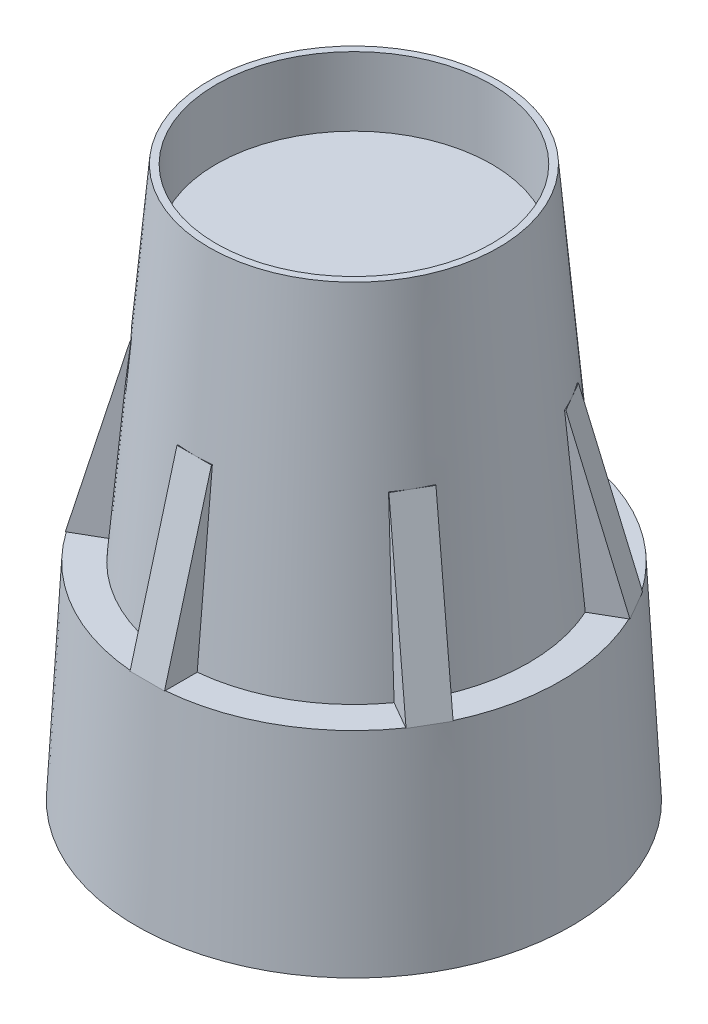
SolidWorks part; units mm, degrees
ref_plane "Front Plane" through (0, 0, 0) normal (0, 0, 1) x (1, 0, 0)
ref_plane "Top Plane" through (0, 0, 0) normal (0, 1, 0) x (1, 0, 0)
ref_plane "Right Plane" through (0, 0, 0) normal (1, 0, 0) x (0, 0, -1)
sketch "Sketch1" plane through (0, 0, 0) normal (0, 1, 0) x (1, 0, 0)
  circle A0 centre (0, 0) radius 21
  dimension "D1" = 42
extrude "Boss-Extrude1" add sketch "Sketch1" against normal blind 50 draft 5 draft outward yes
sketch "Sketch2" plane through (0, -50, 0) normal (0, -1, 0) x (1, 0, 0)
  circle A0 centre (0, 0) radius 30
  dimension "D1" = 60
extrude "Boss-Extrude2" add sketch "Sketch2" along normal blind 30 draft 3 draft outward yes
sketch "Sketch3" plane through (0, 0, 0) normal (1, 0, 0) x (0, 0, -1)
  line L1 (-21, 0) -> (-25.3744, -50) construction
  line L2 (-25.3744, -50) -> (-30, -50)
  line L3 (-30, -50) -> (-23.1872, -25)
  line L4 (-23.1872, -25) -> (-20.2805, -25)
  line L5 (-20.2805, -25) -> (-22.4677, -50)
  line L6 (30, -50) -> (-30, -50) construction
  line L7 (-22.4677, -50) -> (-25.3744, -50)
extrude "Boss-Extrude3" add sketch "Sketch3" along normal mid plane 5
pattern_circular "CirPattern1" count 6 every 60 about axis through (0, 0, 0) along (0, 1, 0) of "Boss-Extrude3"
sketch "Sketch4" plane through (0, -80, 0) normal (0, -1, 0) x (1, 0, 0)
  circle A0 centre (0, 0) radius 27.2913
  circle A1 centre (0, 0) radius 23.5946
extrude "Cut-Extrude1" cut sketch "Sketch4" against normal blind 3 draft 10 contours A0 A1
sketch "Sketch5" plane through (0, -80, 0) normal (0, -1, 0) x (1, 0, 0)
  circle A0 centre (0, 0) radius 19.3823
  circle A1 centre (0, 0) radius 16.1728
extrude "Cut-Extrude2" cut sketch "Sketch5" against normal blind 2.5 draft 10 contours A0 A1
sketch "Sketch6" plane through (0, -80, 0) normal (0, -1, 0) x (1, 0, 0)
  circle A0 centre (0, 0) radius 10.9258
extrude "Boss-Extrude4" add sketch "Sketch6" along normal blind 2.5 draft 30
sketch "Sketch7" plane through (0, 0, 0) normal (0, 1, 0) x (1, 0, 0)
  circle A0 centre (0, 0) radius 20
  dimension "D1" = 40
extrude "Cut-Extrude3" cut sketch "Sketch7" against normal blind 10
